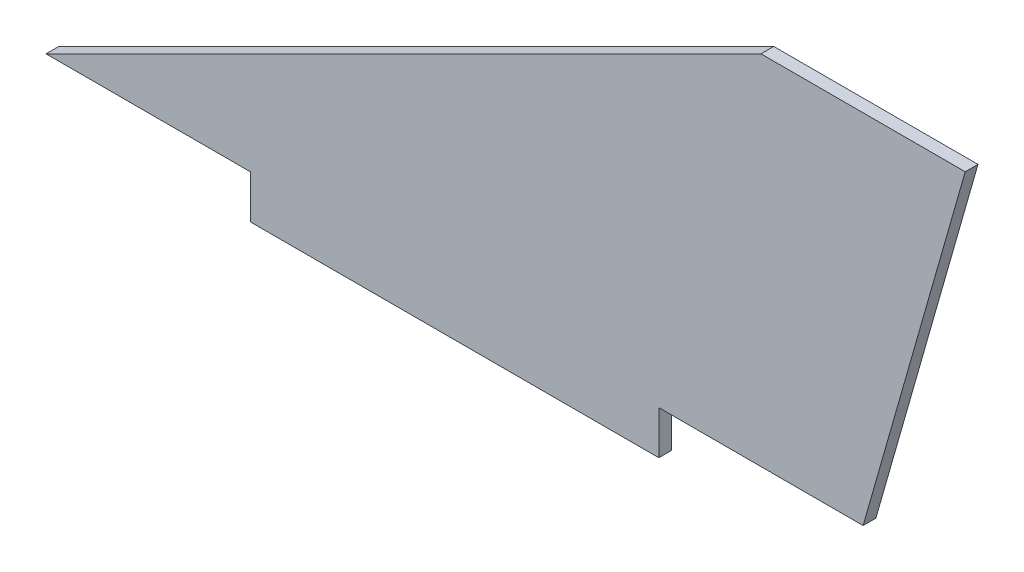
SolidWorks part; units mm, degrees
ref_plane "Front Plane" through (0, 0, 0) normal (0, 0, 1) x (1, 0, 0)
ref_plane "Top Plane" through (0, 0, 0) normal (0, 1, 0) x (1, 0, 0)
ref_plane "Right Plane" through (0, 0, 0) normal (1, 0, 0) x (0, 0, -1)
sketch "Sketch1" plane through (0, 0, 0) normal (0, 0, 1) x (1, 0, 0)
  line L0 (0, 0) -> (50.8, 0)
  line L1 (50.8, 0) -> (50.8, -10.795)
  line L2 (50.8, -10.795) -> (152.4, -10.795)
  line L3 (152.4, -10.795) -> (152.4, 0)
  line L4 (152.4, 0) -> (203.2, 0)
  line L5 (203.2, 0) -> (228.6, 88.9)
  line L6 (228.6, 88.9) -> (177.8, 88.9)
  line L7 (177.8, 88.9) -> (0, 0)
  dimension "D1" = 101.6
  dimension "D2" = 10.795
  dimension "D3" = 10.795
  dimension "D4" = 50.8
  dimension "D5" = 50.8
  dimension "D6" = 88.9
  dimension "D7" = 50.8
  dimension "D8" = 177.8
extrude "Boss-Extrude1" add sketch "Sketch1" along normal blind 3.175
